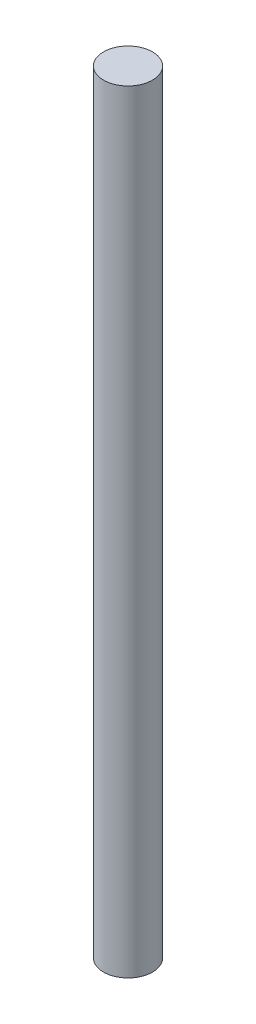
SolidWorks part; units mm, degrees
ref_plane "Front Plane" through (0, 0, 0) normal (0, 0, 1) x (1, 0, 0)
ref_plane "Top Plane" through (0, 0, 0) normal (0, 1, 0) x (1, 0, 0)
ref_plane "Right Plane" through (0, 0, 0) normal (1, 0, 0) x (0, 0, -1)
sketch "Sketch1" plane through (0, 0, 0) normal (0, 1, 0) x (1, 0, 0)
  circle A0 centre (0, 0) radius 6.5
  dimension "D1" = 13
extrude "Boss-Extrude1" add sketch "Sketch1" along normal blind 205
